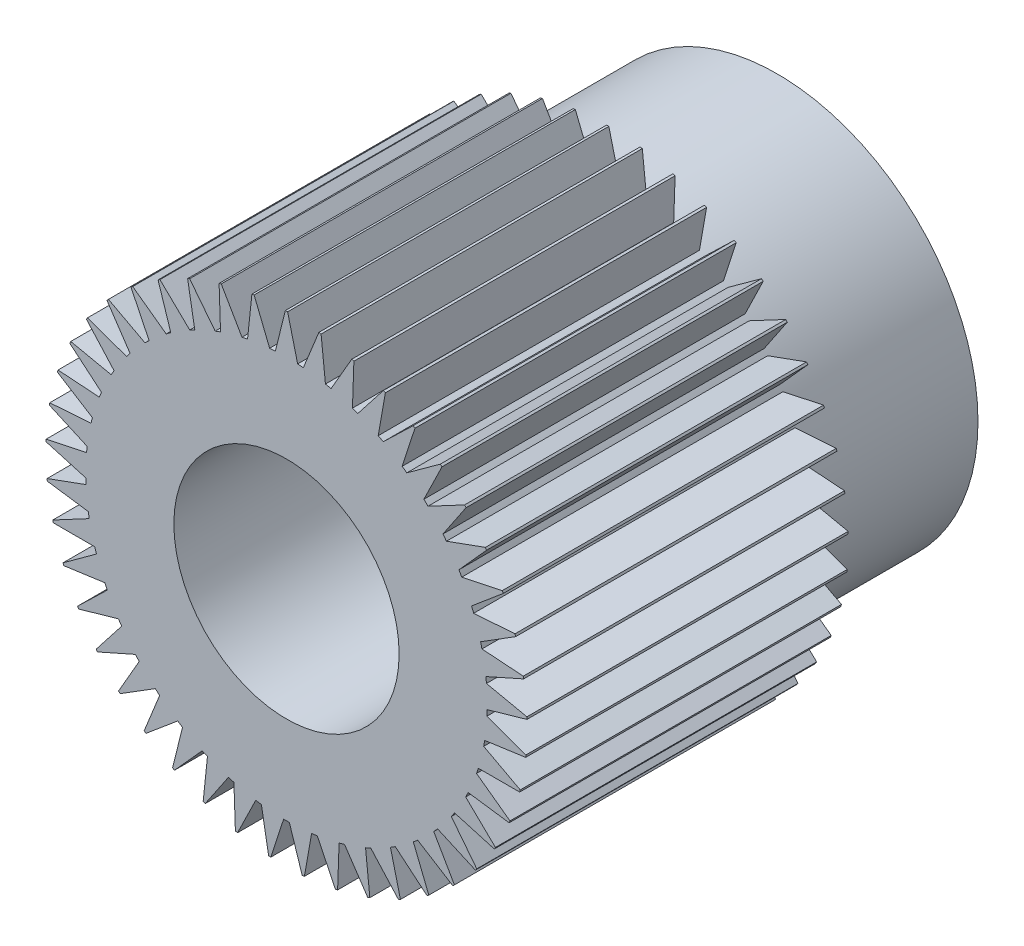
SolidWorks part; units mm, degrees
ref_plane "Front Plane" through (0, 0, 0) normal (0, 0, 1) x (1, 0, 0)
ref_plane "Top Plane" through (0, 0, 0) normal (0, 1, 0) x (1, 0, 0)
ref_plane "Right Plane" through (0, 0, 0) normal (1, 0, 0) x (0, 0, -1)
sketch "Sketch1" plane through (0, 0, 0) normal (0, 0, 1) x (1, 0, 0)
  circle A0 centre (0, 0) radius 4.5
  dimension "D1" = 9
extrude "Boss-Extrude1" add sketch "Sketch1" along normal blind 11
sketch "Sketch2" plane through (0, 0, 11) normal (0, 0, 1) x (1, 0, 0)
  circle A0 centre (0, 0) radius 2.525
  dimension "D1" = 5.05
extrude "Cut-Extrude1" cut sketch "Sketch2" against normal through all
sketch "Sketch3" plane through (0, 0, 11) normal (0, 0, 1) x (1, 0, 0)
  line L0 (-0.25, 4.4931) -> (-0.025, 5.3931)
  line L1 (0.025, 5.3931) -> (0.25, 4.4931)
  line L2 (0, 0) -> (0, 2.525) construction
  line L3 (-0.025, 5.3931) -> (0.025, 5.3931)
  circle A0 centre (0, 0) radius 4.5 construction
  circle A1 centre (0, 0) radius 2.525 construction
  arc A2 (-0.25, 4.4931) -> (0.25, 4.4931) centre (0, 0) cw
  dimension "D1" = 4.5
  dimension "D3" = 0.05
  dimension "D2" = 0.5
  dimension "D4" = 0.9
extrude "Boss-Extrude2" add sketch "Sketch3" against normal blind 7.2
pattern_circular "CirPattern2" count 45 every 8 about axis through (0, 0, 0) along (0, 0, 1) of "Boss-Extrude2"
